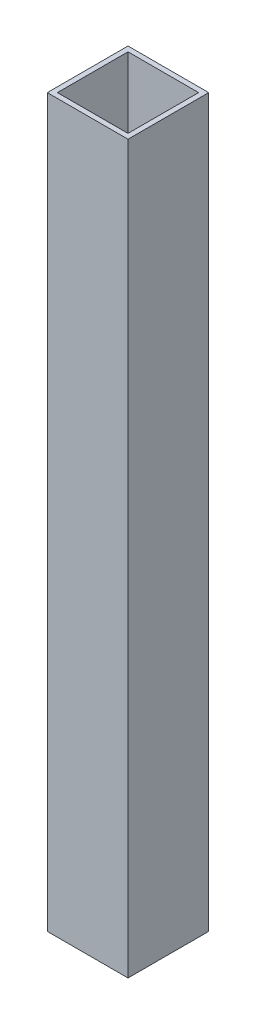
SolidWorks part; units mm, degrees
material "1060 Alloy"
ref_plane "Front Plane" through (0, 0, 0) normal (0, 0, 1) x (1, 0, 0)
ref_plane "Top Plane" through (0, 0, 0) normal (0, 1, 0) x (1, 0, 0)
ref_plane "Right Plane" through (0, 0, 0) normal (1, 0, 0) x (0, 0, -1)
sketch "Sketch1" plane through (0, 0, 0) normal (0, 1, 0) x (1, 0, 0)
  line L1 (12.7, 12.7) -> (-12.7, 12.7)
  line L2 (12.7, 12.7) -> (12.7, -12.7)
  line L3 (12.7, -12.7) -> (-12.7, -12.7)
  line L4 (-12.7, 12.7) -> (-12.7, -12.7)
  line L5 (12.7, 12.7) -> (-12.7, -12.7) construction
  line L6 (12.7, -12.7) -> (-12.7, 12.7) construction
  line L7 (11.1125, 11.1125) -> (-11.1125, 11.1125)
  line L8 (11.1125, 11.1125) -> (11.1125, -11.1125)
  line L9 (11.1125, -11.1125) -> (-11.1125, -11.1125)
  line L10 (-11.1125, 11.1125) -> (-11.1125, -11.1125)
  line L11 (11.1125, 11.1125) -> (-11.1125, -11.1125) construction
  line L12 (11.1125, -11.1125) -> (-11.1125, 11.1125) construction
  point P0 (0, 0)
  point P6 (0, 0)
  dimension "D1" = 25.4
  dimension "D2" = 25.4
  dimension "D3" = 1.5875
  dimension "D4" = 1.5875
extrude "Boss-Extrude1" add sketch "Sketch1" along normal blind 228.6
